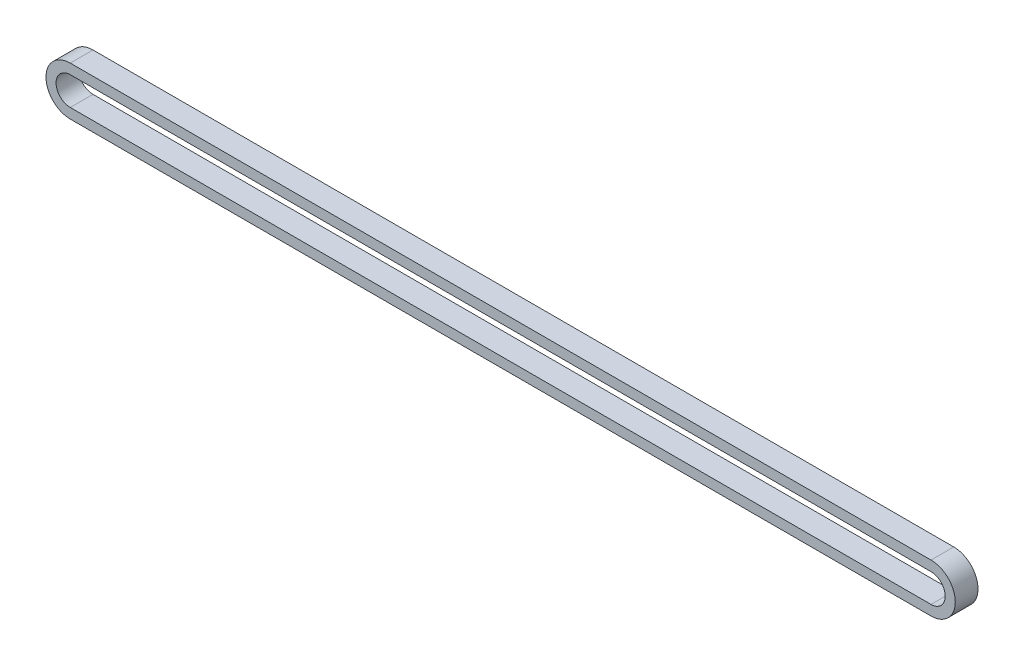
SolidWorks part; units mm, degrees
material "Rubber"
ref_plane "Front Plane" through (0, 0, 0) normal (0, 0, 1) x (1, 0, 0)
ref_plane "Top Plane" through (0, 0, 0) normal (0, 1, 0) x (1, 0, 0)
ref_plane "Right Plane" through (0, 0, 0) normal (1, 0, 0) x (0, 0, -1)
sketch "Sketch1" plane through (0, 0, 0) normal (0, 0, 1) x (1, 0, 0)
  line L0 (0, 3.2) -> (113.6, 3.2)
  line L1 (0, -3.2) -> (113.6, -3.2)
  line L2 (0, 1.872) -> (113.6, 1.872)
  line L3 (0, -1.872) -> (113.6, -1.872)
  circle A0 centre (0, 0) radius 1.872 construction
  arc A1 (0, 1.872) -> (0, -1.872) centre (0, 0) ccw
  circle A2 centre (0, 0) radius 3.2 construction
  arc A3 (0, 3.2) -> (0, -3.2) centre (0, 0) ccw
  circle A4 centre (113.6, 0) radius 3.2 construction
  circle A5 centre (113.6, 0) radius 1.872 construction
  arc A6 (113.6, -3.2) -> (113.6, 3.2) centre (113.6, 0) ccw
  arc A7 (113.6, -1.872) -> (113.6, 1.872) centre (113.6, 0) ccw
extrude "Boss-Extrude1" add sketch "Sketch1" along normal blind 3 contours L0 A6 L1 A3
